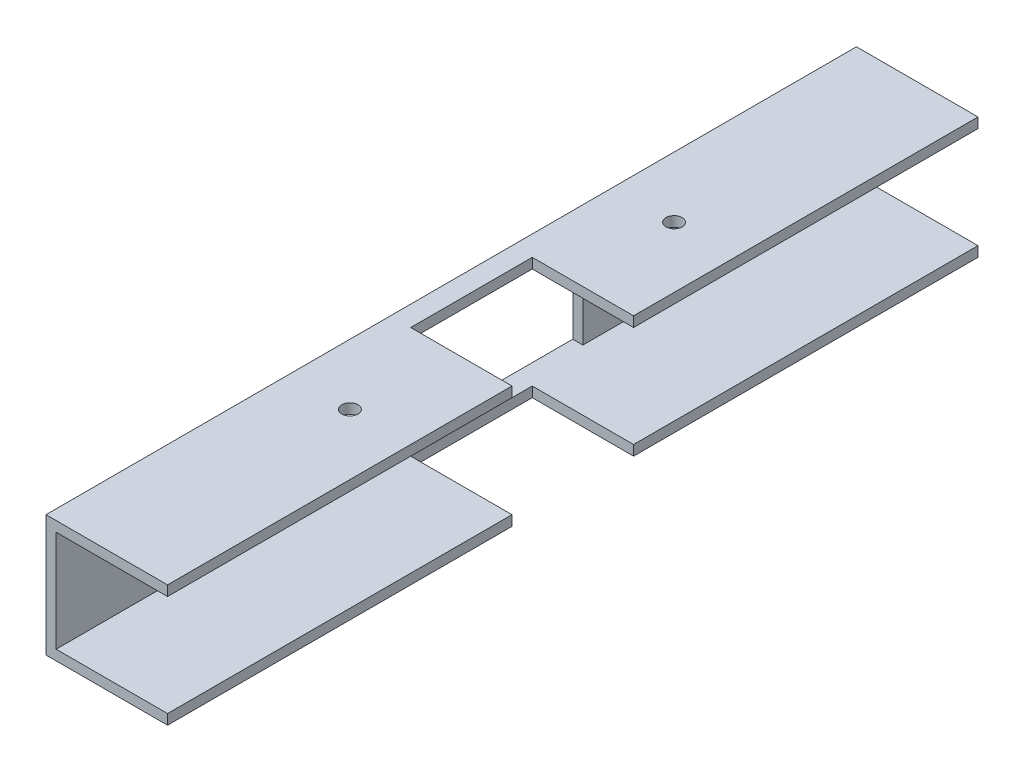
SolidWorks part; units mm, degrees
ref_plane "Front Plane" through (0, 0, 0) normal (0, 0, 1) x (1, 0, 0)
ref_plane "Top Plane" through (0, 0, 0) normal (0, 1, 0) x (1, 0, 0)
ref_plane "Right Plane" through (0, 0, 0) normal (1, 0, 0) x (0, 0, -1)
sketch "Sketch1" plane through (0, 0, 0) normal (0, 0, 1) x (1, 0, 0)
  line L0 (19.05, 19.05) -> (-19.05, 19.05)
  line L1 (-19.05, 19.05) -> (-19.05, -19.05)
  line L2 (-19.05, -19.05) -> (19.05, -19.05)
  line L3 (19.05, 15.875) -> (-15.875, 15.875)
  line L4 (-15.875, 15.875) -> (-15.875, -15.875)
  line L5 (-15.875, -15.875) -> (19.05, -15.875)
  line L6 (19.05, 19.05) -> (19.05, 15.875)
  line L7 (19.05, -15.875) -> (19.05, -19.05)
  line L8 (19.05, -19.05) -> (19.2107, -19.0871)
  dimension "D1" = 38.1
  dimension "D3" = 19.05
  dimension "D4" = 19.05
  dimension "D2" = 3.175
extrude "Boss-Extrude1" add sketch "Sketch1" along normal mid plane 254 contours L7 L5 L4 L3 L6 L0 L1 L2
sketch "Sketch2" plane through (0, 19.05, 0) normal (0, 1, 0) x (1, 0, 0)
  line L0 (19.05, -127) -> (19.05, 127) construction
  line L1 (19.05, 19.05) -> (-12.7, 19.05)
  line L2 (19.05, 19.05) -> (19.05, -19.05)
  line L3 (19.05, -19.05) -> (-12.7, -19.05)
  line L4 (-12.7, 19.05) -> (-12.7, -19.05)
  line L6 (-20.955, 0) -> (20.955, 0) construction
  point P6 (-12.7, 0)
  dimension "D1" = 38.1
  dimension "D2" = 31.75
extrude "Cut-Extrude1" cut sketch "Sketch2" against normal through all
sketch "Sketch3" plane through (-19.05, 0, 0) normal (-1, 0, 0) x (0, 0, 1)
  line L0 (127, 19.05) -> (-127, 19.05) construction
  line L1 (-38.1, 15.875) -> (38.1, 15.875)
  line L2 (-38.1, 15.875) -> (-38.1, -15.875)
  line L3 (-38.1, -15.875) -> (38.1, -15.875)
  line L4 (38.1, 15.875) -> (38.1, -15.875)
  dimension "D1" = 76.2
  dimension "D2" = 31.75
  dimension "D3" = 3.175
  dimension "D4" = 19.05
extrude "Cut-Extrude2" cut sketch "Sketch3" against normal through all
sketch "Sketch4" plane through (0, 19.05, 0) normal (0, 1, 0) x (1, 0, 0)
  line L0 (-12.7, -19.05) -> (19.05, -19.05) construction
  circle A0 centre (0, -50.8) radius 2.54
  dimension "D1" = 31.75
extrude "Cut-Extrude3" cut sketch "Sketch4" against normal up to next
mirror "Mirror1" about plane through (0, 0, 0) normal (0, 0, 1) of "Cut-Extrude3"
